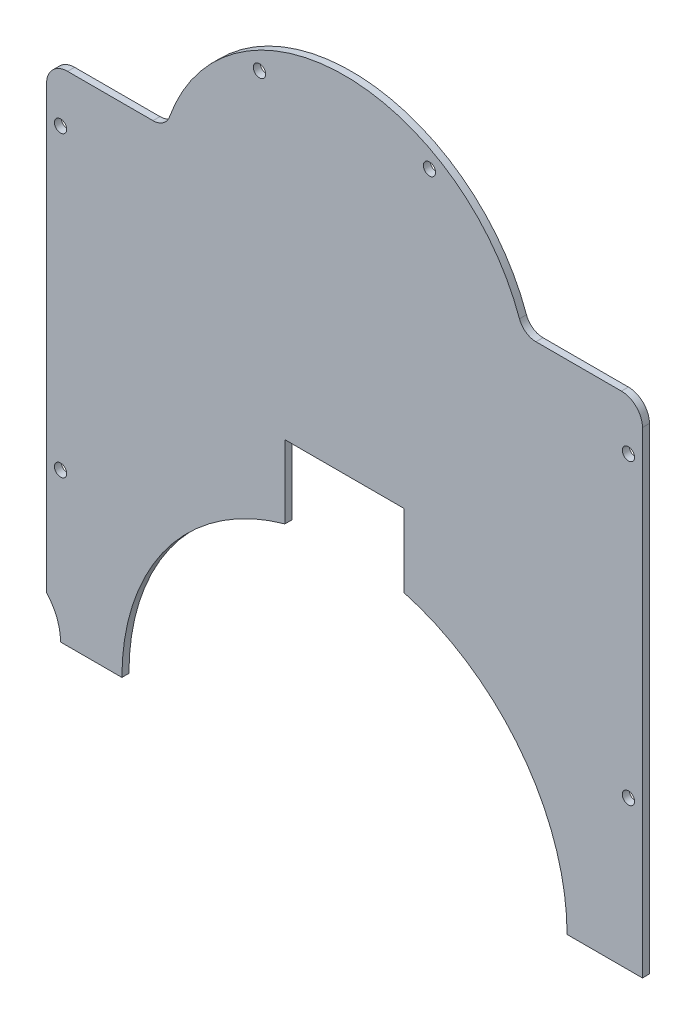
SolidWorks part; units mm, degrees
material "PVC"
ref_plane "Plan de face" through (0, 0, 0) normal (0, 0, 1) x (1, 0, 0)
ref_plane "Plan de dessus" through (0, 0, 0) normal (0, 1, 0) x (1, 0, 0)
ref_plane "Plan de droite" through (0, 0, 0) normal (1, 0, 0) x (0, 0, -1)
sketch "Esquisse1" plane through (0, 0, 0) normal (0, 0, 1) x (1, 0, 0)
  line L0 (79, 142) -> (54.6237, 142)
  line L1 (85, 0) -> (85, 136)
  line L2 (-85, 136) -> (-85, 10.198)
  line L3 (-54.6237, 142) -> (-79, 142)
  line L4 (-174.7519, 0) -> (85, 0) construction
  line L5 (-63.5, 0) -> (-81, 0)
  line L6 (85, 0) -> (63.5, 0)
  line L7 (0, 127.5) -> (0, -109.5308) construction
  line L8 (-17, 61.1821) -> (-17, 82)
  line L9 (-17, 82) -> (17, 82)
  line L10 (17, 82) -> (17, 61.1821)
  line L11 (0, 127.5) -> (-24.25, 169.5022) construction
  arc A0 (49.9148, 145.319) -> (54.6237, 142) centre (54.6237, 147) ccw
  arc A1 (85, 136) -> (79, 142) centre (79, 136) ccw
  arc A2 (-79, 142) -> (-85, 136) centre (-79, 136) ccw
  arc A3 (-54.6237, 142) -> (-49.9148, 145.319) centre (-54.6237, 147) ccw
  arc A4 (49.9148, 145.319) -> (-49.9148, 145.319) centre (0, 127.5) ccw
  arc A5 (-63.5, 0) -> (-17, 61.1821) centre (0, 0) cw
  arc A6 (17, 61.1821) -> (63.5, 0) centre (0, 0) cw
  arc A7 (-85, 10.198) -> (-81, 0) centre (-96, 0) cw
  circle A8 centre (-81, 42.5) radius 1.75
  circle A9 centre (-81, 127.5) radius 1.75
  circle A10 centre (-24.25, 169.5022) radius 1.75
  circle A11 centre (24.25, 169.5022) radius 1.75
  circle A12 centre (81, 127.5) radius 1.75
  circle A13 centre (81, 42.5) radius 1.75
  dimension "D4" = 63.5
  dimension "D8" = 53
  dimension "D2" = 85
  dimension "D7" = 127.5
  dimension "D11" = 6
  dimension "D12" = 5
  dimension "D13" = 6
  dimension "D14" = 5
  dimension "D10" = 15
  dimension "D17" = 3.5
  dimension "D3" = 82
  dimension "D5" = 34
  dimension "D6" = 17
  dimension "D9" = 85
  dimension "D15" = 142
  dimension "D16" = 166
  dimension "D18" = 42.5
  dimension "D19" = 81
  dimension "D20" = 85
  dimension "D21" = 48.5
  dimension "D22" = 30
extrude "Extrusion1" add sketch "Esquisse1" along normal blind 2
